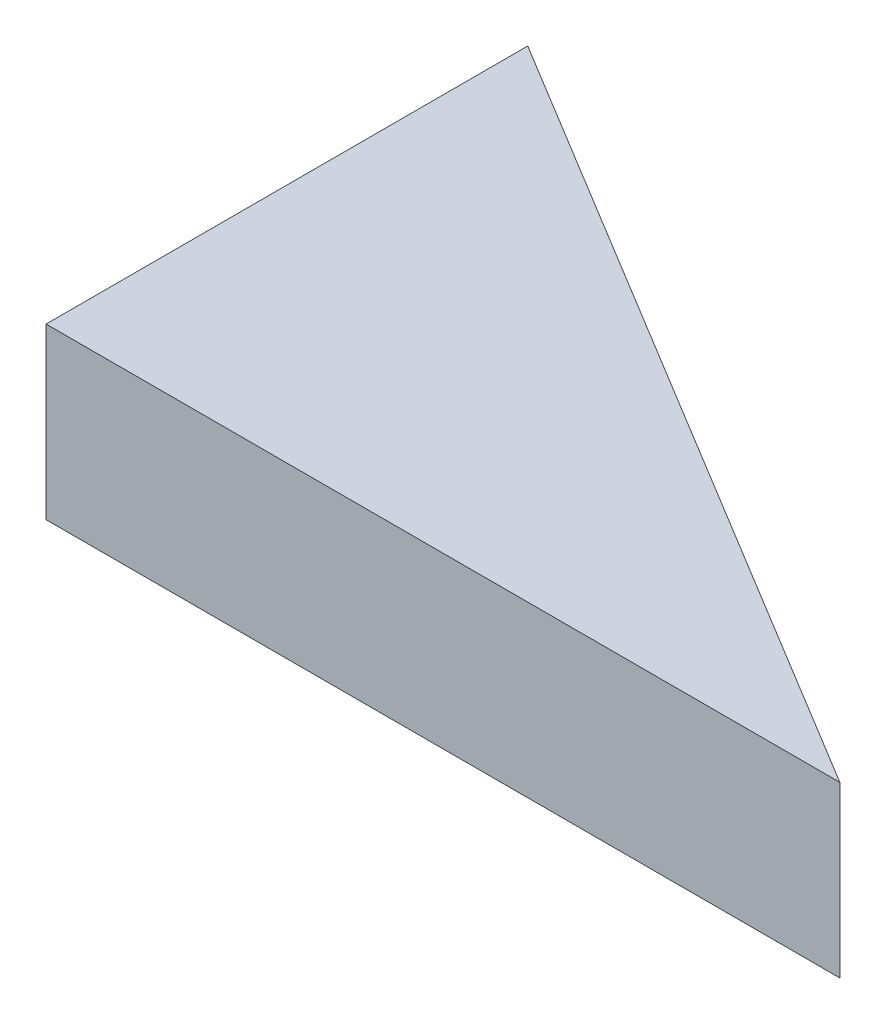
SolidWorks part; units mm, degrees
material "Polyurethane Foam Flexible"
ref_plane "Front Plane" through (0, 0, 0) normal (0, 0, 1) x (1, 0, 0)
ref_plane "Top Plane" through (0, 0, 0) normal (0, 1, 0) x (1, 0, 0)
ref_plane "Right Plane" through (0, 0, 0) normal (1, 0, 0) x (0, 0, -1)
sketch "Sketch1" plane through (0, 0, 0) normal (0, 1, 0) x (1, 0, 0)
  line L0 (0, 0) -> (0, 137.16)
  line L1 (0, 137.16) -> (226.06, 0)
  line L2 (226.06, 0) -> (0, 0)
  dimension "D1" = 137.16
  dimension "D2" = 226.06
extrude "Boss-Extrude1" add sketch "Sketch1" along normal blind 48.26
